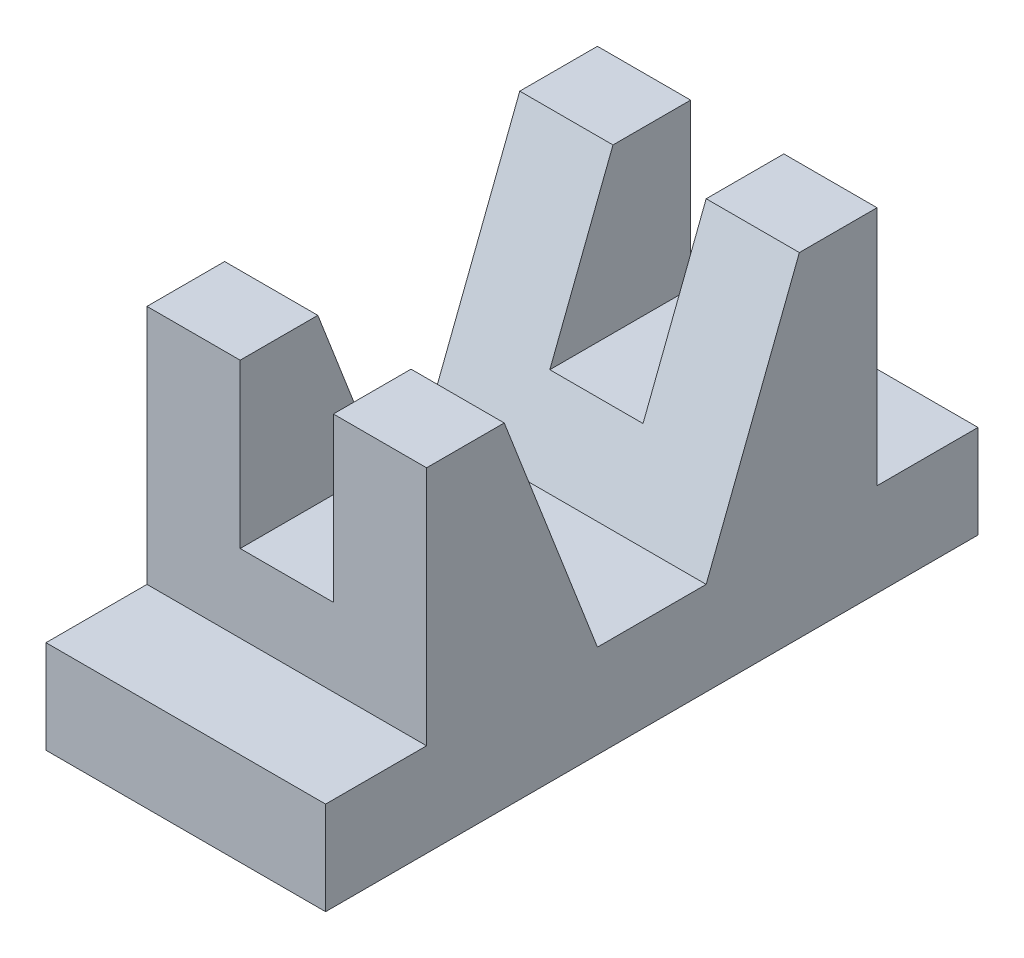
SolidWorks part; units mm, degrees
ref_plane "Alzado" through (0, 0, 0) normal (0, 0, 1) x (1, 0, 0)
ref_plane "Planta" through (0, 0, 0) normal (0, 1, 0) x (1, 0, 0)
ref_plane "Vista lateral" through (0, 0, 0) normal (1, 0, 0) x (0, 0, -1)
sketch "Croquis1" plane through (0, 0, 0) normal (1, 0, 0) x (0, 0, -1)
  line L0 (0, 0) -> (0, 27.5398) construction
  line L1 (42, 0) -> (-42, 0)
  line L2 (-42, 0) -> (-42, 12)
  line L3 (-42, 12) -> (-29, 12)
  line L4 (-29, 12) -> (-29, 43)
  line L5 (-29, 43) -> (-19, 43)
  line L6 (-19, 43) -> (-7, 12)
  line L7 (-7, 12) -> (7, 12)
  line L8 (29, 43) -> (19, 43)
  line L9 (19, 43) -> (7, 12)
  line L10 (42, 0) -> (42, 12)
  line L11 (42, 12) -> (29, 12)
  line L12 (29, 12) -> (29, 43)
  point P13 (0, 12)
  point P17 (-35.5, 12)
  dimension "D1" = 84
  dimension "D2" = 12
  dimension "D3" = 58
  dimension "D4" = 14
  dimension "D5" = 38
  dimension "D6" = 31
extrude "Saliente-Extruir1" add sketch "Croquis1" along normal blind 36
sketch "Croquis2" plane through (0, 0, 29) normal (0, 0, 1) x (1, 0, 0)
  line L0 (36, 43) -> (0, 43) construction
  line L1 (36, 12) -> (0, 12) construction
  line L2 (12, 43) -> (24, 43)
  line L3 (12, 43) -> (12, 22)
  line L4 (12, 22) -> (24, 22)
  line L5 (24, 43) -> (24, 22)
  point P8 (18, 43)
  point P9 (18, 12)
  dimension "D1" = 10
  dimension "D2" = 12
extrude "Cortar-Extruir1" cut sketch "Croquis2" against normal through all
